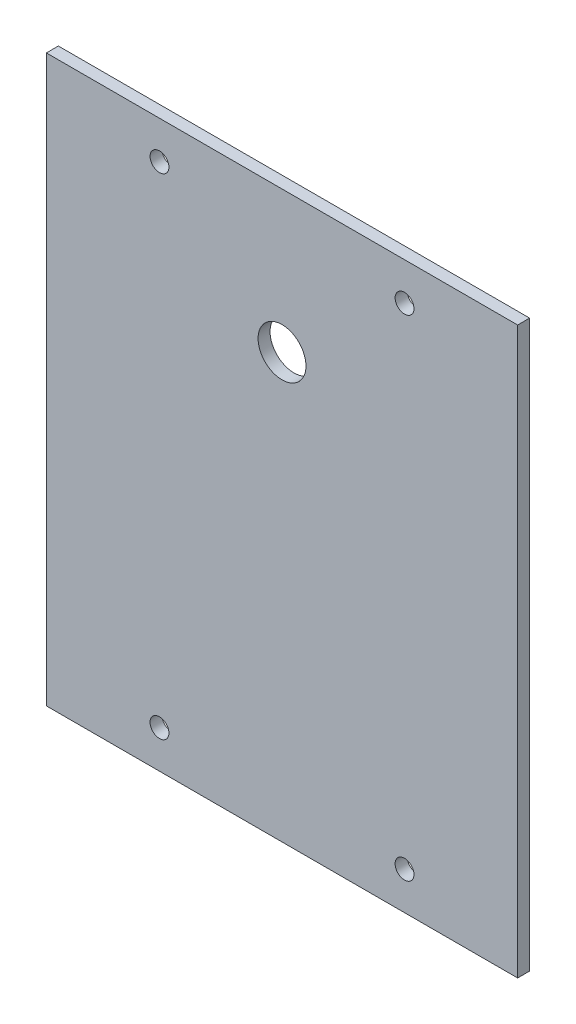
SolidWorks part; units mm, degrees
material "Custom Plastic"
ref_plane "Front Plane" through (0, 0, 0) normal (0, 0, 1) x (1, 0, 0)
ref_plane "Top Plane" through (0, 0, 0) normal (0, 1, 0) x (1, 0, 0)
ref_plane "Right Plane" through (0, 0, 0) normal (1, 0, 0) x (0, 0, -1)
sketch "Sketch1" plane through (0, 0, 0) normal (0, 0, 1) x (1, 0, 0)
  line L1 (-125, 150) -> (0, 150)
  line L2 (-125, 150) -> (-125, 0)
  line L3 (-125, 0) -> (0, 0)
  line L4 (0, 150) -> (0, 0)
  dimension "D1" = 150
  dimension "D2" = 125
extrude "Boss-Extrude1" add sketch "Sketch1" along normal blind 3.175
sketch "Sketch2" plane through (0, 0, 3.175) normal (0, 0, 1) x (1, 0, 0)
  line L0 (-125, 150) -> (-125, 0) construction
  line L1 (0, 0) -> (0, 150) construction
  line L2 (0, 150) -> (-125, 150) construction
  circle A0 centre (-95, 140) radius 2.5
  circle A1 centre (-30, 140) radius 2.5
  dimension "D1" = 5
  dimension "D2" = 5
  dimension "D3" = 30
  dimension "D4" = 30
  dimension "D5" = 10
  dimension "D6" = 10
extrude "Cut-Extrude1" cut sketch "Sketch2" against normal up to surface (3.175 mm away) up to face at (-62.5, 75, 0)
ref_plane "Plane1" through (0, 75, 0) normal (0, 1, 0) x (1, 0, 0)
mirror "Mirror1" about plane through (0, 75, 0) normal (0, 1, 0) of "Cut-Extrude1"
sketch "Sketch3" plane through (0, 0, 3.175) normal (0, 0, 1) x (1, 0, 0)
  line L0 (1.7463, 75) -> (-1.7463, 75) construction
  line L1 (-125, 112.5) -> (0, 112.5) construction
  line L2 (-62.5, 0) -> (-62.5, 75) construction
  line L5 (-125, 75) -> (0, 75) construction
  line L6 (-125, 150) -> (-125, 0) construction
  line L7 (0, 0) -> (0, 150) construction
  line L8 (-125, 0) -> (0, 0) construction
  line L9 (-62.5, 75) -> (-62.5, 150) construction
  line L10 (0, 150) -> (-125, 150) construction
  circle A2 centre (-62.5, 112.5) radius 6.35
  dimension "D1" = 12.7
  dimension "D2" = 37.5
extrude "Cut-Extrude2" cut sketch "Sketch3" against normal up to surface (3.175 mm away) up to face at (-92.5, 10, 0)
